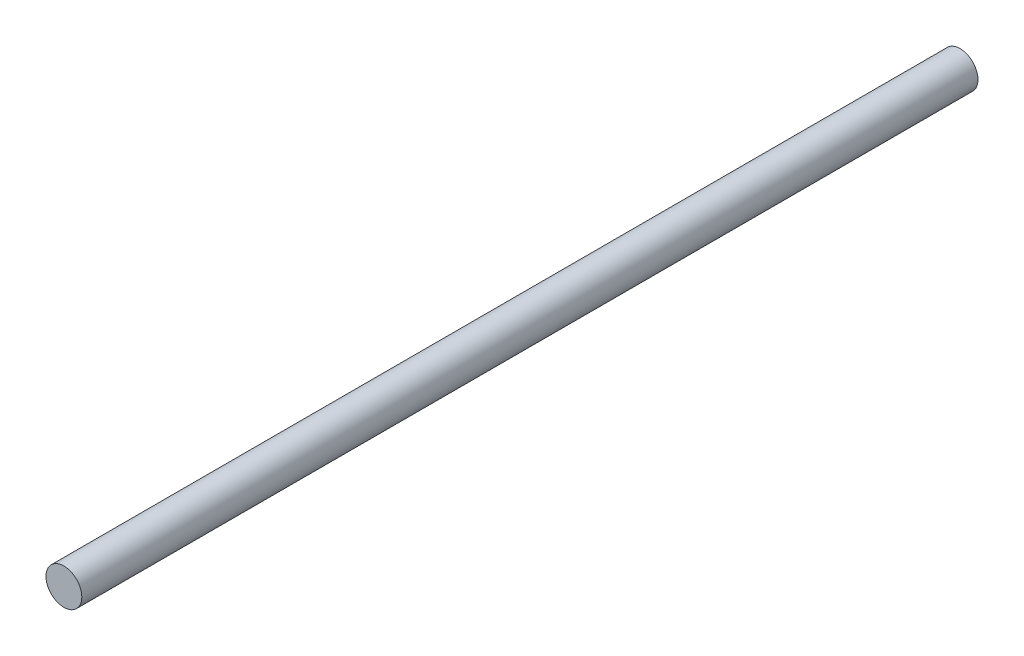
SolidWorks part; units mm, degrees
ref_plane "Front Plane" through (0, 0, 0) normal (0, 0, 1) x (1, 0, 0)
ref_plane "Top Plane" through (0, 0, 0) normal (0, 1, 0) x (1, 0, 0)
ref_plane "Right Plane" through (0, 0, 0) normal (1, 0, 0) x (0, 0, -1)
sketch "Sketch1" plane through (0, 0, 0) normal (0, 0, 1) x (1, 0, 0)
  circle A0 centre (0, 0) radius 5
  dimension "D1" = 10
extrude "Boss-Extrude1" add sketch "Sketch1" along normal blind 250
